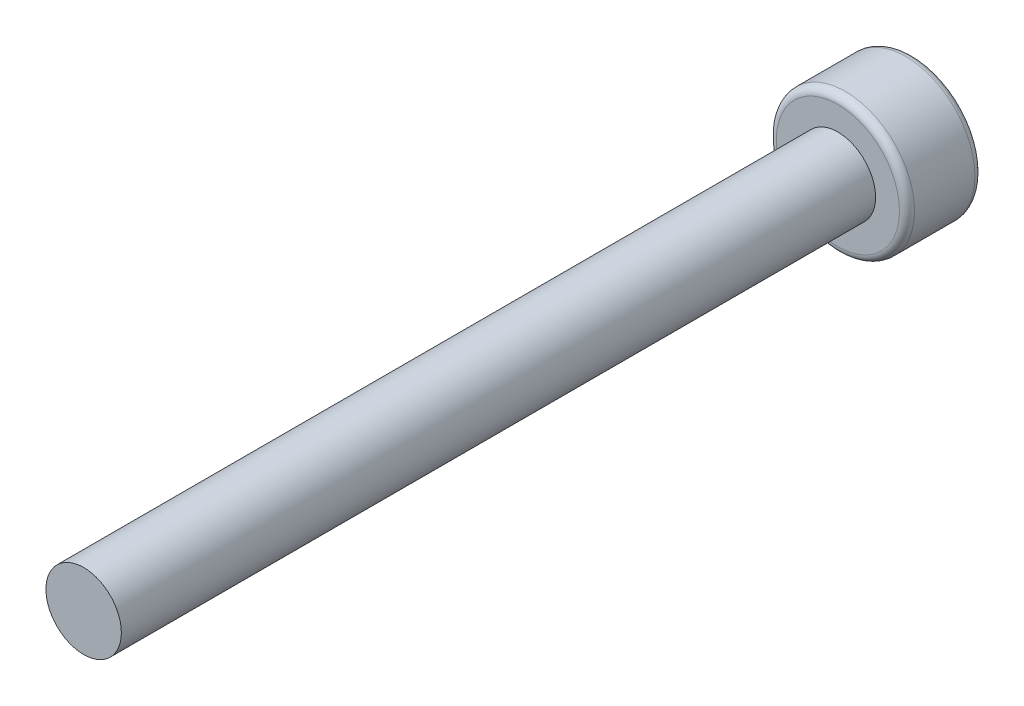
SolidWorks part; units mm, degrees
ref_plane "前视基准面" through (0, 0, 0) normal (0, 0, 1) x (1, 0, 0)
ref_plane "上视基准面" through (0, 0, 0) normal (0, 1, 0) x (1, 0, 0)
ref_plane "右视基准面" through (0, 0, 0) normal (1, 0, 0) x (0, 0, -1)
sketch "草图1" plane through (0, 0, 0) normal (0, 0, 1) x (1, 0, 0)
  circle A0 centre (0, 0) radius 2.75
  dimension "D1" = 2.75
extrude "凸台-拉伸1" add sketch "草图1" along normal blind 3
sketch "草图2" plane through (0, 0, 3) normal (0, 0, 1) x (1, 0, 0)
  circle A0 centre (0, 0) radius 1.5
  dimension "D1" = 1.5
extrude "凸台-拉伸2" add sketch "草图2" along normal blind 30
cosmetic thread "装饰螺纹线1" parameters "D2"=2
fillet "圆角1" radius 0.3 2 edges at (2.75, 0, 0) (2.75, 0, 3)
sketch "草图3" plane through (0, 0, 0) normal (0, 0, -1) x (-1, 0, 0)
  line L1 (-0.8209, 1.8624) -> (-2.0233, 0.2203)
  line L2 (-2.0233, 0.2203) -> (-1.2025, -1.6421)
  line L3 (-1.2025, -1.6421) -> (0.8209, -1.8624)
  line L4 (0.8209, -1.8624) -> (2.0233, -0.2203)
  line L5 (2.0233, -0.2203) -> (1.2025, 1.6421)
  line L6 (1.2025, 1.6421) -> (-0.8209, 1.8624)
  circle A0 centre (0, 0) radius 1.7626 construction
extrude "切除-拉伸1" cut sketch "草图3" against normal blind 2
